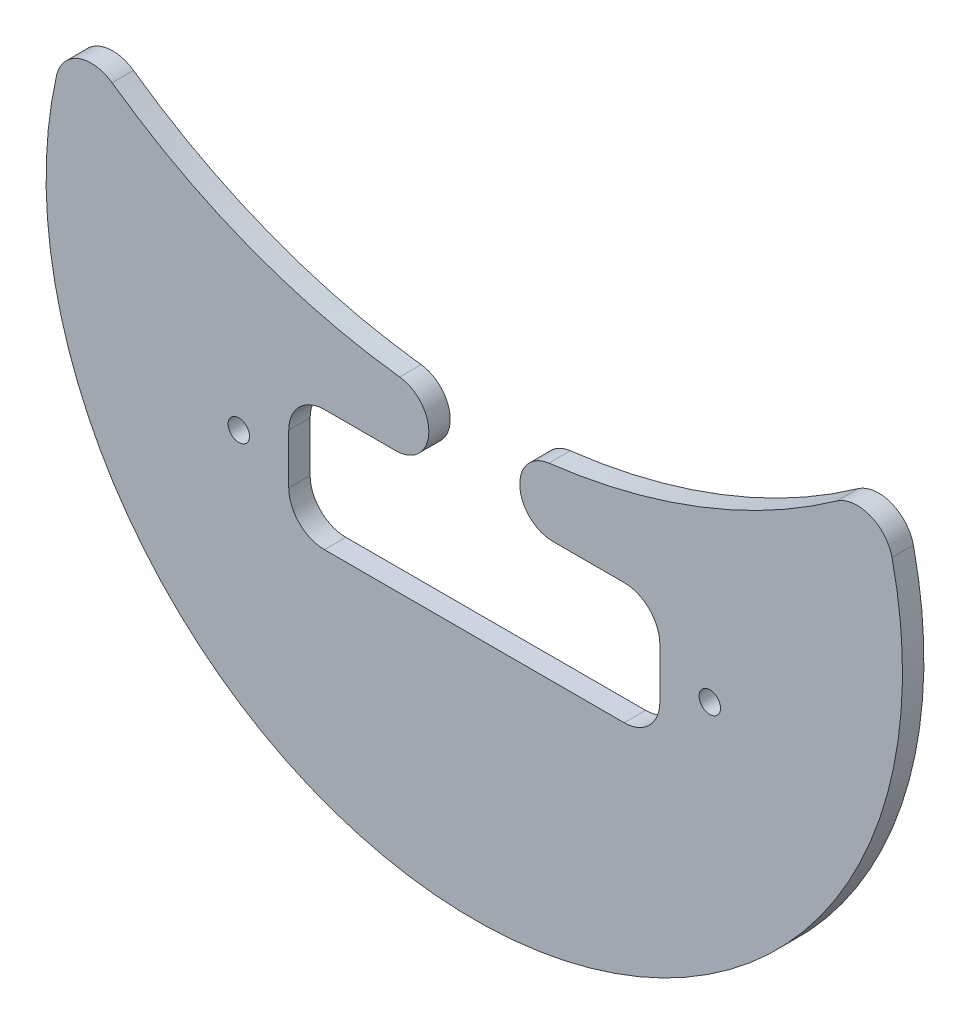
SolidWorks part; units mm, degrees
ref_plane "Front Plane" through (0, 0, 0) normal (0, 0, 1) x (1, 0, 0)
ref_plane "Top Plane" through (0, 0, 0) normal (0, 1, 0) x (1, 0, 0)
ref_plane "Right Plane" through (0, 0, 0) normal (1, 0, 0) x (0, 0, -1)
sketch "Sketch1" plane through (0, 0, 0) normal (0, 0, 1) x (1, 0, 0)
  line L1 (0.1514, 32.35) -> (0.1514, 52.6395) construction
  line L2 (-25.8486, 6.75) -> (26.1514, 6.75)
  line L3 (-25.8486, 6.75) -> (-25.8486, 23.75)
  line L4 (-25.8486, 23.75) -> (-10.8486, 23.75)
  line L5 (26.1514, 6.75) -> (26.1514, 23.75)
  line L6 (11.1514, 23.75) -> (26.1514, 23.75)
  arc A0 (-56.2301, 52.8712) -> (56.533, 52.8712) centre (0.1514, 32.35) ccw
  arc A1 (-56.2301, 52.8712) -> (-10.2972, 32.9745) centre (0.1514, 120.0641) ccw
  arc A2 (-10.2972, 32.9745) -> (-10.8486, 23.75) centre (-10.8486, 28.3788) cw
  arc A3 (10.6, 32.9745) -> (11.1514, 23.75) centre (11.1514, 28.3788) ccw
  arc A4 (10.6, 32.9745) -> (56.533, 52.8712) centre (0.1514, 120.0641) ccw
  circle A5 centre (-32.8486, 15.25) radius 1.5
  circle A6 centre (33.1514, 15.25) radius 1.5
  point P3 (0.1514, 32.35)
  point P8 (0.1514, -27.65)
  dimension "D2" = 60
  dimension "D3" = 140
  dimension "D5" = 3
  dimension "D4" = 15
extrude "Boss-Extrude1" add sketch "Sketch1" along normal blind 3
fillet "Fillet4" radius 5 6 edges at (-25.8486, 23.75, 1.5) (-25.8486, 6.75, 1.5) (26.1514, 6.75, 1.5) (26.1514, 23.75, 1.5) (-56.2301, 52.8712, 1.5) (56.533, 52.8712, 1.5)
